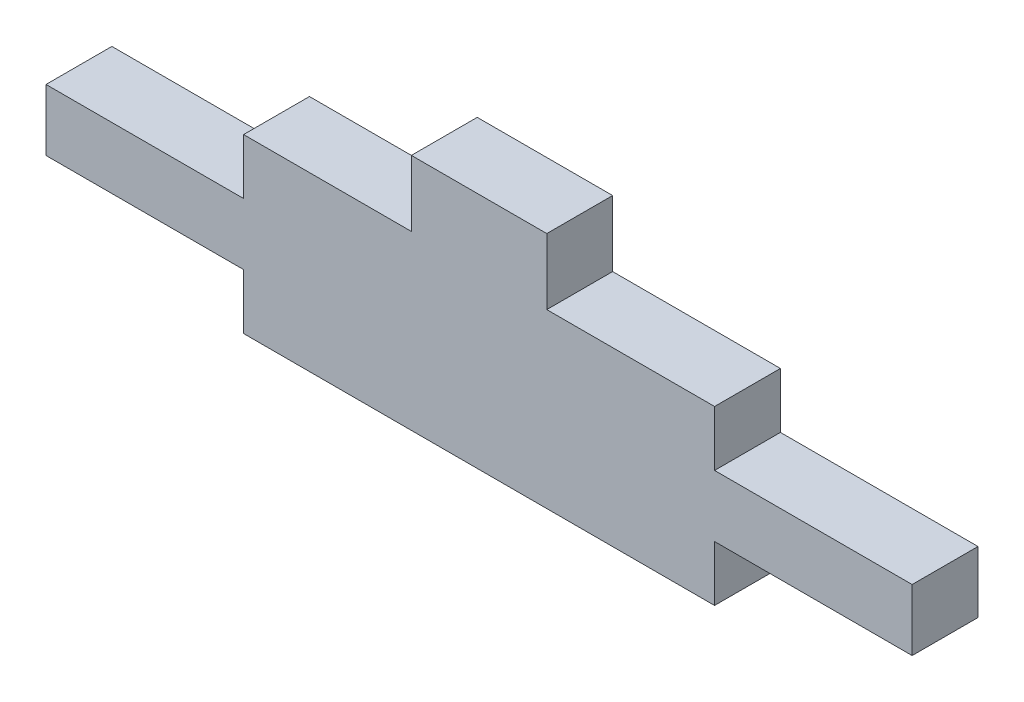
SolidWorks part; units mm, degrees
ref_plane "Front Plane" through (0, 0, 0) normal (0, 0, 1) x (1, 0, 0)
ref_plane "Top Plane" through (0, 0, 0) normal (0, 1, 0) x (1, 0, 0)
ref_plane "Right Plane" through (0, 0, 0) normal (1, 0, 0) x (0, 0, -1)
sketch "Model" plane through (0, 0, 0) normal (0, 0, 1) x (1, 0, 0)
  line L16 (0, 0) -> (0, 19.35) construction
  line L18 (-19.13, 0) -> (19.13, 0)
  line L19 (-19.13, 0) -> (-19.13, 4.5)
  line L20 (-19.13, 14) -> (-5.5, 14)
  line L21 (19.13, 0) -> (19.13, 4.5)
  line L22 (35.18, 9.5) -> (35.18, 4.5)
  line L23 (-5.5, 14) -> (-5.5, 19.35)
  line L24 (-5.5, 19.35) -> (5.5, 19.35)
  line L25 (5.5, 14) -> (5.5, 19.35)
  line L26 (5.5, 14) -> (19.13, 14)
  line L27 (-19.13, 9.5) -> (-35.18, 9.5)
  line L28 (19.13, 9.5) -> (19.13, 14)
  line L29 (-19.13, 4.5) -> (-35.18, 4.5)
  line L30 (-35.18, 9.5) -> (-35.18, 4.5)
  line L31 (19.13, 4.5) -> (35.18, 4.5)
  line L33 (19.13, 9.5) -> (35.18, 9.5)
  line L34 (-19.13, 9.5) -> (-19.13, 14)
  point P30 (0, 19.35)
  dimension "D3" = 38.26
  dimension "D4" = 14
  dimension "D5" = 5.35
  dimension "D7" = 11
  dimension "D9" = 16.05
  dimension "D11" = 5
  dimension "D14" = 4.5
extrude "Boss-Extrude1" add sketch "Model" along normal blind 5.35
equation "\"mdfthick\"=5.35"
equation "\"D5@Model\"=\"mdfthick\""
equation "\"D1@Boss-Extrude1\"=\"mdfthick\""
